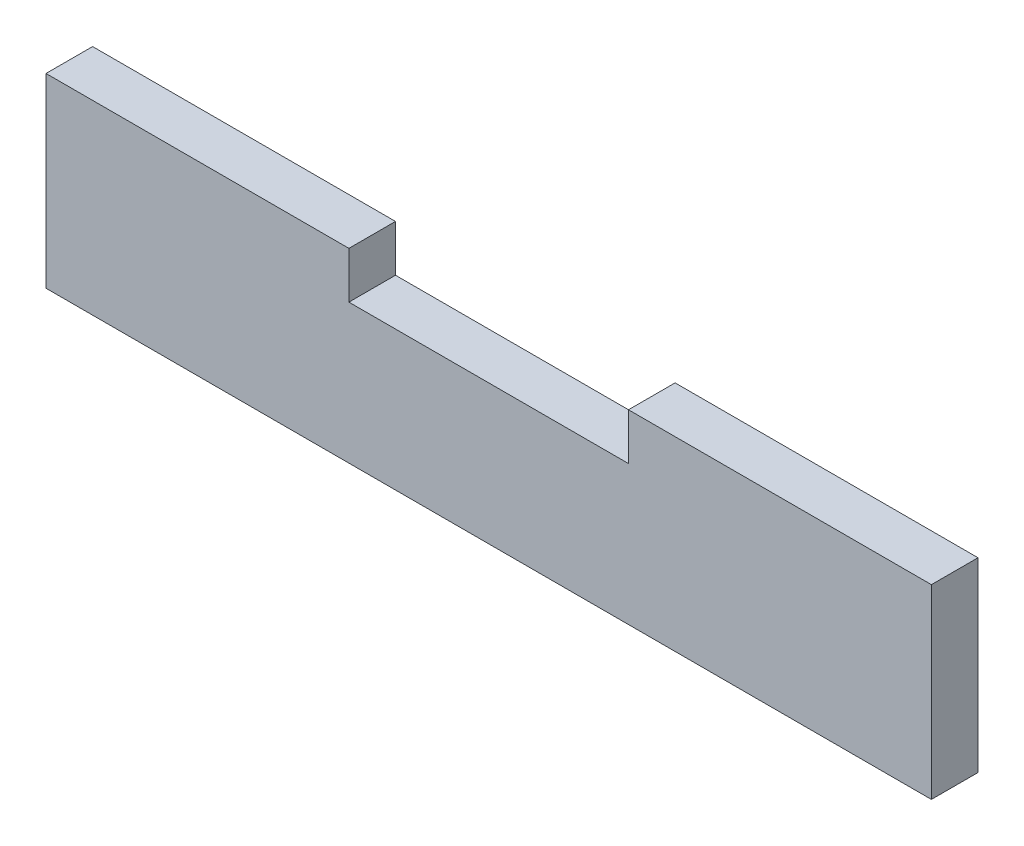
SolidWorks part; units mm, degrees
ref_plane "Front Plane" through (0, 0, 0) normal (0, 0, 1) x (1, 0, 0)
ref_plane "Top Plane" through (0, 0, 0) normal (0, 1, 0) x (1, 0, 0)
ref_plane "Right Plane" through (0, 0, 0) normal (1, 0, 0) x (0, 0, -1)
sketch "Model" plane through (0, 0, 0) normal (0, 0, 1) x (1, 0, 0)
  line L0 (-19.05, 0) -> (19.05, 0)
  line L1 (19.05, 0) -> (19.05, 6.35)
  line L2 (60.325, 6.35) -> (19.05, 6.35)
  line L3 (60.325, -19) -> (60.325, 6.35)
  line L4 (-60.325, -19) -> (60.325, -19)
  line L5 (-60.325, 6.35) -> (-60.325, -19)
  line L6 (-19.05, 6.35) -> (-60.325, 6.35)
  line L7 (-19.05, 6.35) -> (-19.05, 0)
  point P8 (0, 0)
  point P9 (0, 0)
  point P11 (-60.325, -12.6929)
  dimension "D1" = 25.35
  dimension "D2" = 120.65
  dimension "D3" = 38.1
  dimension "D4" = 6.35
extrude "Boss-Extrude1" add sketch "Model" along normal blind 6.35
